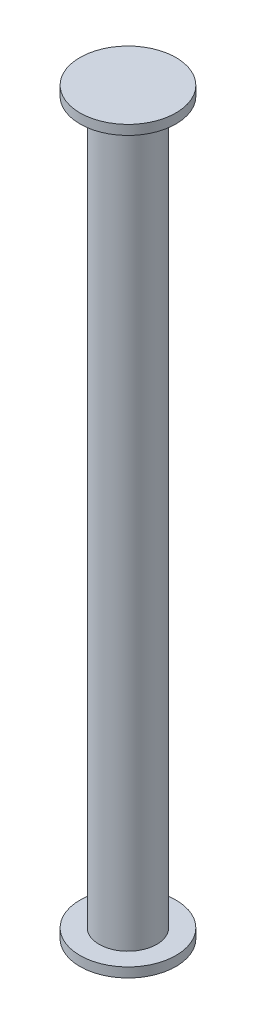
SolidWorks part; units mm, degrees
ref_plane "Front Plane" through (0, 0, 0) normal (0, 0, 1) x (1, 0, 0)
ref_plane "Top Plane" through (0, 0, 0) normal (0, 1, 0) x (1, 0, 0)
ref_plane "Right Plane" through (0, 0, 0) normal (1, 0, 0) x (0, 0, -1)
sketch "Sketch3" plane through (0, 0, 0) normal (0, 1, 0) x (1, 0, 0)
  circle A0 centre (0, 0) radius 0.5
extrude "Boss-Extrude1" add sketch "Sketch3" along normal blind 0.1
sketch "Sketch4" plane through (0, 0.1, 0) normal (0, 1, 0) x (1, 0, 0)
  circle A0 centre (0, 0) radius 0.3
extrude "Boss-Extrude2" add sketch "Sketch4" along normal blind 7.5 contours A0
sketch "Sketch5" plane through (0, 7.6, 0) normal (0, 1, 0) x (1, 0, 0)
  circle A0 centre (0, 0) radius 0.5
extrude "Boss-Extrude3" add sketch "Sketch5" along normal blind 0.1
